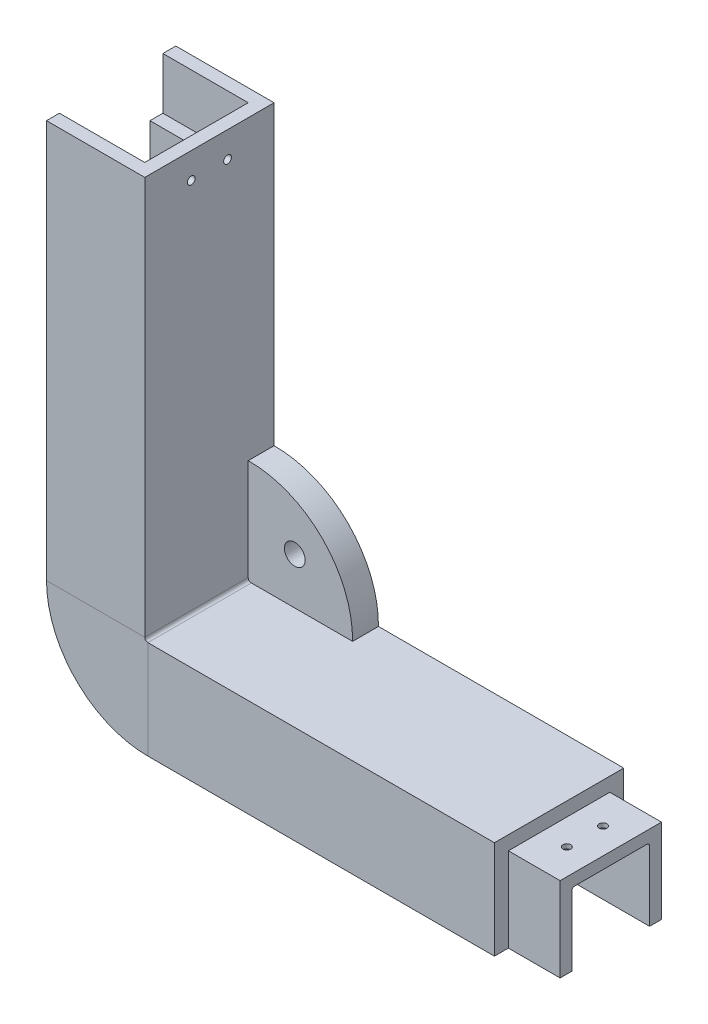
SolidWorks part; units mm, degrees
ref_plane "Front Plane" through (0, 0, 0) normal (0, 0, 1) x (1, 0, 0)
ref_plane "Top Plane" through (0, 0, 0) normal (0, 1, 0) x (1, 0, 0)
ref_plane "Right Plane" through (0, 0, 0) normal (1, 0, 0) x (0, 0, -1)
sketch "Sketch3" plane through (0, 0, 0) normal (0, 1, 0) x (1, 0, 0)
  line L1 (0, -17.4625) -> (0, 17.4625) construction
  line L3 (0, 10.275) -> (-24.13, 10.275)
  line L4 (-24.13, 10.275) -> (-24.13, 3.925)
  line L5 (-24.13, 3.925) -> (-6.985, 3.925)
  line L6 (-6.35, 3.29) -> (-6.35, -14.49)
  line L7 (0, -21.475) -> (-24.13, -21.475)
  line L8 (-24.13, -21.475) -> (-24.13, -15.125)
  line L9 (-24.13, -15.125) -> (-6.985, -15.125)
  line L10 (0, 10.275) -> (0, -21.475)
  arc A0 (-6.35, 3.29) -> (-6.985, 3.925) centre (-6.985, 3.29) ccw
  arc A1 (-6.35, -14.49) -> (-6.985, -15.125) centre (-6.985, -14.49) cw
  point P14 (-6.35, 3.925)
  point P17 (-6.35, -15.125)
  dimension "D7" = 0.635
  dimension "D1" = 6.35
  dimension "D2" = 6.35
  dimension "D3" = 17.78
  dimension "D4" = 6.35
  dimension "D5" = 17.78
  dimension "D6" = 19.05
sketch "Sketch4" plane through (0, 0, 0) normal (0, 0, 1) x (1, 0, 0)
  line L8 (0, 0) -> (0, -85.09)
  line L9 (0.762, -85.852) -> (85.852, -85.852)
  arc A4 (0, -85.09) -> (0.762, -85.852) centre (0.762, -85.09) ccw
  dimension "D2" = 85.09
  dimension "D1" = 85.09
sweep "Sweep1" add profiles "Sketch3" path "Sketch4"
sketch "Sketch6" plane through (85.852, 0, 0) normal (1, 0, 0) x (0, 0, -1)
  line L1 (-15.125, -109.982) -> (-21.475, -109.982) construction
  line L2 (-18.046, -89.281) -> (6.846, -89.281)
  line L6 (3.925, -109.982) -> (3.925, -92.837)
  line L8 (3.29, -92.202) -> (-14.49, -92.202)
  line L10 (-15.125, -92.837) -> (-15.125, -109.982)
  line L12 (3.925, -109.982) -> (6.846, -109.982)
  line L13 (10.275, -109.982) -> (3.925, -109.982) construction
  line L14 (6.846, -109.982) -> (6.846, -89.281)
  line L15 (-15.125, -109.982) -> (-18.046, -109.982)
  line L16 (-18.046, -109.982) -> (-18.046, -89.281)
  arc A0 (-14.49, -92.202) -> (-15.125, -92.837) centre (-14.49, -92.837) ccw
  arc A2 (-14.49, -92.202) -> (-15.125, -92.837) centre (-14.49, -92.837) ccw construction
  arc A3 (3.29, -92.202) -> (3.925, -92.837) centre (3.29, -92.837) cw
  arc A4 (3.925, -92.837) -> (3.29, -92.202) centre (3.29, -92.837) ccw construction
  dimension "D1" = 2.921
  dimension "D2" = 2.921
  dimension "D3" = 2.921
extrude "Boss-Extrude2" add sketch "Sketch6" along normal blind 12.7
sketch "Sketch7" plane through (0, 0, 0) normal (0, 1, 0) x (1, 0, 0)
  line L0 (-24.13, 7.1) -> (-24.13, 10.275)
  line L1 (-24.13, 10.275) -> (-24.13, 3.925) construction
  line L2 (-24.13, 10.275) -> (0, 10.275)
  line L3 (0, 10.275) -> (0, -21.475)
  line L4 (0, -21.475) -> (-24.13, -21.475)
  line L5 (-24.13, -21.475) -> (-24.13, -18.3)
  line L6 (-24.13, -21.475) -> (-24.13, -15.125) construction
  line L7 (-24.13, -18.3) -> (-3.175, -18.3)
  line L8 (-3.175, -18.3) -> (-3.175, 7.1)
  line L9 (-3.175, 7.1) -> (-24.13, 7.1)
  dimension "D1" = 3.175
extrude "Boss-Extrude3" add sketch "Sketch7" along normal blind 12.7
sketch "Sketch8" plane through (0, -92.202, 0) normal (0, -1, 0) x (1, 0, 0)
  line L1 (0.762, 15.125) -> (98.552, 15.125) construction
  line L2 (98.552, 14.49) -> (98.552, -3.29) construction
  line L4 (0.762, -3.925) -> (98.552, -3.925) construction
  circle A0 centre (92.202, 10.045) radius 0.9525
  circle A1 centre (92.202, 1.155) radius 0.9525
  dimension "D1" = 5.08
  dimension "D3" = 5.08
  dimension "D5" = 1.905
  dimension "D6" = 1.905
  dimension "D2" = 6.35
  dimension "D4" = 6.35
extrude "Cut-Extrude1" cut sketch "Sketch8" against normal through all
sketch "Sketch9" plane through (-3.175, 0, 0) normal (-1, 0, 0) x (0, 0, 1)
  line L0 (-7.1, 12.7) -> (18.3, 12.7) construction
  line L3 (-3.925, 0) -> (-3.925, -85.09) construction
  line L4 (15.125, 0) -> (15.125, -85.09) construction
  circle A0 centre (1.155, 6.35) radius 0.9525
  circle A1 centre (10.045, 6.35) radius 0.9525
  dimension "D1" = 6.35
  dimension "D5" = 1.905
  dimension "D6" = 1.905
  dimension "D2" = 6.35
  dimension "D3" = 5.08
  dimension "D4" = 5.08
extrude "Cut-Extrude2" cut sketch "Sketch9" against normal through all
sketch "Sketch12" plane through (0, 0, -10.275) normal (0, 0, 1) x (1, 0, 0)
  line L0 (0, 12.7) -> (0, -85.09) construction
  line L1 (0.762, -85.852) -> (85.852, -85.852) construction
  line L2 (0, -60.2298) -> (0, -85.09)
  line L3 (25.6222, -85.852) -> (0.762, -85.852)
  line L4 (0.762, -109.982) -> (0.762, -85.852) construction
  arc A0 (0, -85.09) -> (0.762, -85.852) centre (0.762, -85.09) ccw construction
  arc A1 (0, -60.2298) -> (25.6222, -85.852) centre (0.2232, -85.6288) cw
  arc A3 (0, -85.09) -> (0.762, -85.852) centre (0.762, -85.09) ccw
  circle A4 centre (11.43, -74.422) radius 2.5527
  dimension "D1" = 11.43
  dimension "D3" = 25.4
  dimension "D2" = 11.43
extrude "Boss-Extrude10" add sketch "Sketch12" along normal blind 6.35
hole_wizard "CSK for #6 Flat Head Machine Screw (100)1" positions "Sketch13" profile "Sketch14" countersink size "#6" standard "ANSI Inch"
sketch "Sketch13" plane through (0, -92.202, 0) normal (0, -1, 0) x (-1, 0, 0)
  point P0 (-92.202, -1.155)
sketch "Sketch14" plane through (92.202, -92.202, 1.155) normal (1, 0, 0) x (0, 0, -1)
  line L0 (0, 0) -> (0, 2.4108)
  line L1 (0, 2.4108) -> (1.8986, 1.27)
  line L2 (1.8986, 1.27) -> (1.8986, 1.38)
  line L3 (1.8986, 1.38) -> (3.5433, 0)
  line L5 (3.5433, 0) -> (0, 0)
  line L6 (-1.8987, 1.38) -> (-3.5433, 0) construction
  line L10 (0, 2.4108) -> (-1.8987, 1.27) construction
  line L11 (0, -6.35) -> (0, 107.95) construction
  dimension "Hole Dia." = 3.7973
  dimension "Hole Depth" = 1.27
  dimension "Near C'Sink Dia." = 7.0866
  dimension "Near C'Sink Angle" = 100
  dimension "Drill Angle" = 118
hole_wizard "CSK for #6 Flat Head Machine Screw (100)2" positions "Sketch15" profile "Sketch16" countersink size "#6" standard "ANSI Inch"
sketch "Sketch15" plane through (0, -92.202, 0) normal (0, -1, 0) x (-1, 0, 0)
  point P0 (-92.202, -10.045)
sketch "Sketch16" plane through (92.202, -92.202, 10.045) normal (1, 0, 0) x (0, 0, -1)
  line L0 (0, 0) -> (0, 2.4108)
  line L1 (0, 2.4108) -> (1.8986, 1.27)
  line L2 (1.8986, 1.27) -> (1.8986, 1.38)
  line L3 (1.8986, 1.38) -> (3.5433, 0)
  line L5 (3.5433, 0) -> (0, 0)
  line L6 (-1.8986, 1.38) -> (-3.5433, 0) construction
  line L10 (0, 2.4108) -> (-1.8986, 1.27) construction
  line L11 (0, -6.35) -> (0, 107.95) construction
  dimension "Hole Dia." = 3.7973
  dimension "Hole Depth" = 1.27
  dimension "Near C'Sink Dia." = 7.0866
  dimension "Near C'Sink Angle" = 100
  dimension "Drill Angle" = 118
